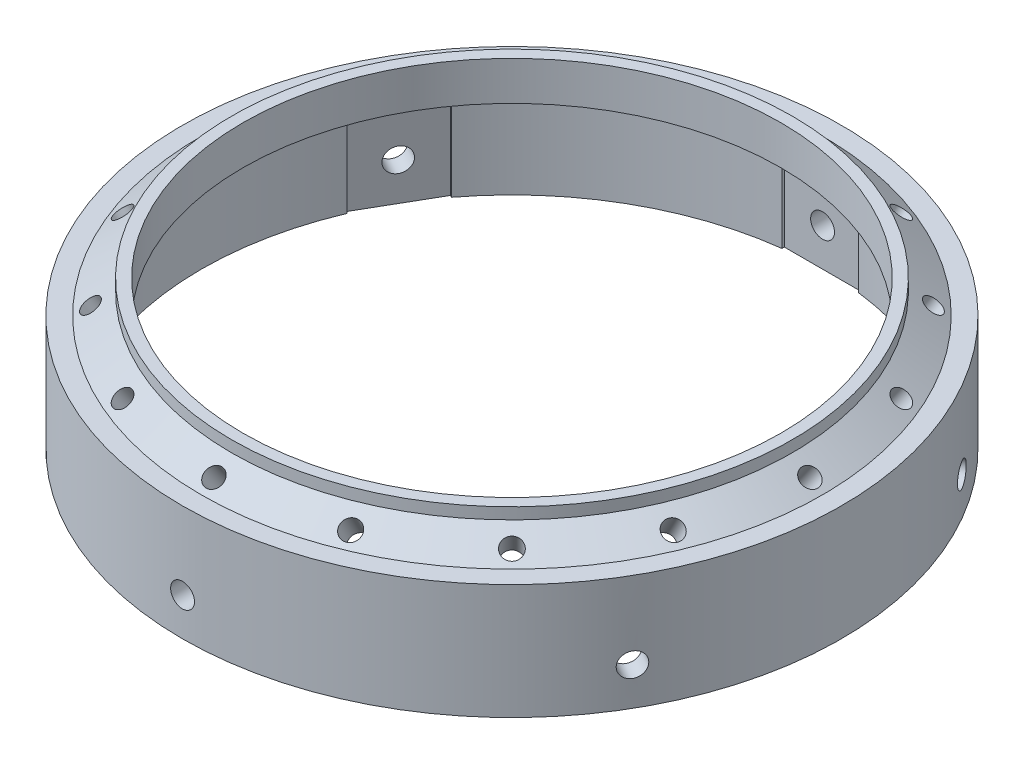
SolidWorks part; units mm, degrees
material "6061 Alloy"
ref_plane "Front Plane" through (0, 0, 0) normal (0, 0, 1) x (1, 0, 0)
ref_plane "Top Plane" through (0, 0, 0) normal (0, 1, 0) x (1, 0, 0)
ref_plane "Right Plane" through (0, 0, 0) normal (1, 0, 0) x (0, 0, -1)
sketch "Sketch1" plane through (0, 0, 0) normal (0, 0, 1) x (1, 0, 0)
  line L9 (0, 0) -> (0, -25.8501) construction
  line L18 (-87, 1) -> (-82, 1)
  line L19 (-82, 1) -> (-74, 6.6017)
  line L20 (-74, 6.6017) -> (-74, 9.6017)
  line L21 (-74, 9.6017) -> (-71, 9.6017)
  line L33 (-71, 9.6017) -> (-71, -0.6981)
  line L34 (-82, -8.4004) -> (-71, -0.6981)
  line L39 (-82, -8.4004) -> (-82, -29.4004)
  line L41 (-82, -29.4004) -> (-87, -29.4004)
  line L42 (-87, -29.4004) -> (-87, 1)
  dimension "D8" = 3
  dimension "D11" = 3
  dimension "D12" = 5
revolve "Revolve1" add sketch "Sketch1" angle 360 about L9
sketch "Sketch2" plane through (0, 0, 0) normal (0, 0, 1) x (1, 0, 0)
  line L0 (-74, 6.6017) -> (-82, 1) construction
  line L1 (-74, 6.6017) -> (-74, 1) construction
  line L2 (-74, 1) -> (-82, 1) construction
  point P4 (-78.671, 3.331)
  dimension "D1" = 4.671
hole_wizard "Ø4.2mm Dowel Hole1" positions "3DSketch1" profile "Sketch3" hole size "Ø5.0" standard "DIN" end condition up to next
sketch3d "3DSketch1"
  point P0 (-78.671, 3.331, 0)
sketch "Sketch3" plane through (-78.671, 3.331, 0) normal (0, 0, 1) x (-0.8192, -0.5736, 0)
  line L0 (0, 0) -> (0, 7.7004)
  line L1 (0, 7.7004) -> (2.5, 7.7004)
  line L2 (2.5, 7.7004) -> (2.5, 0)
  line L5 (2.5, 0) -> (0, 0)
  line L11 (0, -6.35) -> (0, 107.95) construction
  dimension "Thru Hole Dia." = 5
  dimension "Thru Hole Depth" = 7.7004
pattern_circular "CirPattern1" count 16 over 360 about axis through (0, 6.6017, 0) along (0, -1, 0) of "Ø4.2mm Dowel Hole1"
sketch "Szkic4" plane through (0, -29.4004, 0) normal (0, -1, 0) x (-1, 0, 0)
  line L0 (-4, -87) -> (4, -87)
  line L1 (0, -87) -> (0, -84.0434)
  line L2 (0, -84.0434) -> (4, -85.4333)
  line L3 (4, -85.4333) -> (4, -87)
  line L4 (-4, -85.4333) -> (-4, -87)
  line L5 (0, -84.0434) -> (-4, -85.4333)
  line L31 (-77.3442, -40.0359) -> (-73.3442, -46.9641)
  line L32 (-71.9874, -46.1808) -> (-73.3442, -46.9641)
  line L33 (-72.7837, -42.0217) -> (-71.9874, -46.1808)
  line L34 (-72.7837, -42.0217) -> (-75.9874, -39.2526)
  line L35 (-75.9874, -39.2526) -> (-77.3442, -40.0359)
  line L36 (-73.3442, 46.9641) -> (-77.3442, 40.0359)
  line L37 (-75.9874, 39.2526) -> (-77.3442, 40.0359)
  line L38 (-72.7837, 42.0217) -> (-75.9874, 39.2526)
  line L39 (-72.7837, 42.0217) -> (-71.9874, 46.1808)
  line L40 (-71.9874, 46.1808) -> (-73.3442, 46.9641)
  line L41 (4, 87) -> (-4, 87)
  line L42 (-4, 85.4333) -> (-4, 87)
  line L43 (0, 84.0434) -> (-4, 85.4333)
  line L44 (0, 84.0434) -> (4, 85.4333)
  line L45 (4, 85.4333) -> (4, 87)
  line L46 (77.3442, 40.0359) -> (73.3442, 46.9641)
  line L47 (71.9874, 46.1808) -> (73.3442, 46.9641)
  line L48 (72.7837, 42.0217) -> (71.9874, 46.1808)
  line L49 (72.7837, 42.0217) -> (75.9874, 39.2526)
  line L50 (75.9874, 39.2526) -> (77.3442, 40.0359)
  line L51 (73.3442, -46.9641) -> (77.3442, -40.0359)
  line L52 (75.9874, -39.2526) -> (77.3442, -40.0359)
  line L53 (72.7837, -42.0217) -> (75.9874, -39.2526)
  line L54 (72.7837, -42.0217) -> (71.9874, -46.1808)
  line L55 (71.9874, -46.1808) -> (73.3442, -46.9641)
  line L56 (0, 82) -> (-10.1, 82)
  line L57 (-10.1, 82) -> (-10.1, 79.6554)
  line L58 (-10.1, 79.6554) -> (10.1, 79.6554)
  line L59 (10.1, 79.6554) -> (10.1, 82)
  line L60 (10.1, 82) -> (0, 82)
  circle A0 centre (0, 0) radius 87 construction
  circle A1 centre (0, 0) radius 82 construction
  point P37 (0, 0)
  point P38 (0, 0)
  dimension "D1" = 6
sketch "Szkic2" plane through (0, 0, 0) normal (0, 0, 1) x (1, 0, 0)
  line L0 (0, -29.4004) -> (0, -19.4004)
  line L1 (-87, -29.4004) -> (87, -29.4004) construction
  circle A0 centre (0, -19.4004) radius 3.15
extrude "Wytnij-wyciągnięcie1" cut sketch "Szkic2" along normal blind 103 contours A0
pattern_circular "Szyk kołowy1" count 6 over 360 about axis through (0, 0, 0) along (0, 1, 0) of "Wytnij-wyciągnięcie1"
extrude "Wytnij-wyciągnięcie2" cut sketch "Szkic4" against normal blind 21 contours L60 L56 L57 L58 L59
pattern_circular "Szyk kołowy2" count 6 over 360 about axis through (0, 0, 0) along (0, 1, 0) of "Wytnij-wyciągnięcie2"
equation "\"D1@Sketch2\"=4+cos(35)*cos(35)"
